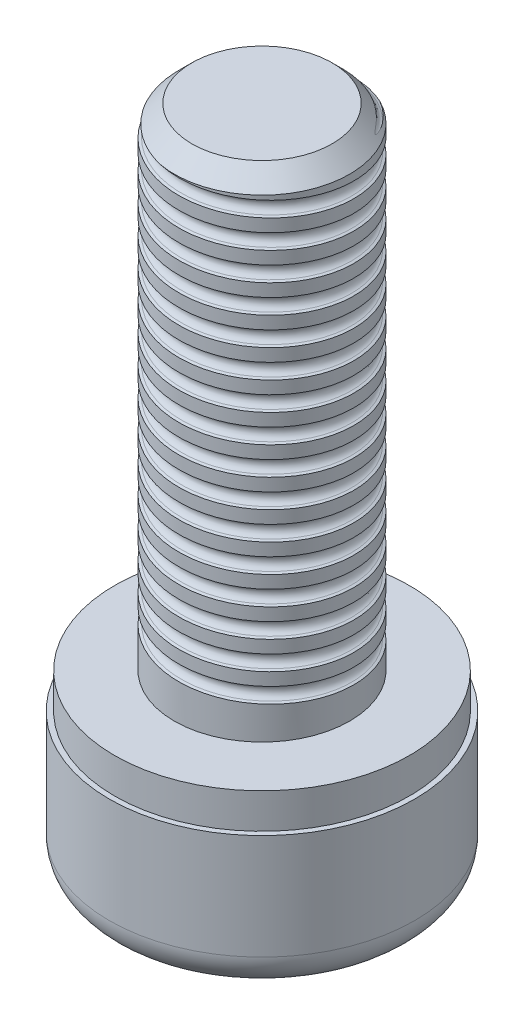
SolidWorks part; units mm, degrees
ref_plane "Спереди" through (0, 0, 0) normal (0, 0, 1) x (1, 0, 0)
ref_plane "Сверху" through (0, 0, 0) normal (0, 1, 0) x (1, 0, 0)
ref_plane "Справа" through (0, 0, 0) normal (1, 0, 0) x (0, 0, -1)
sketch "Эскиз1" plane through (0, 0, 0) normal (0, 1, 0) x (1, 0, 0)
  circle A0 centre (0, 0) radius 4.35
  dimension "D1" = 8.7
extrude "Бобышка-Вытянуть1" add sketch "Эскиз1" along normal blind 5
sketch "Эскиз2" plane through (0, 5, 0) normal (0, 1, 0) x (1, 0, 0)
  circle A0 centre (0, 0) radius 2.5
  dimension "D1" = 5
extrude "Бобышка-Вытянуть2" add sketch "Эскиз2" along normal blind 14
chamfer "Фаска1" distance 0.5 angle 45 1 edges at (0, 19, 2.5)
sketch "Эскиз3" plane through (0, 0, 0) normal (0, -1, 0) x (1, 0, 0)
  line L1 (1.9892, -1.1731) -> (2.0106, 1.1362)
  line L2 (2.0106, 1.1362) -> (0.0214, 2.3093)
  line L3 (0.0214, 2.3093) -> (-1.9892, 1.1731)
  line L4 (-1.9892, 1.1731) -> (-2.0106, -1.1362)
  line L5 (-2.0106, -1.1362) -> (-0.0214, -2.3093)
  line L6 (-0.0214, -2.3093) -> (1.9892, -1.1731)
  circle A0 centre (0, 0) radius 2 construction
  dimension "D1" = 4
extrude "Вырез-Вытянуть1" cut sketch "Эскиз3" against normal blind 2.5
fillet "Скругление1" radius 1 1 edges at (0, 0, 4.35)
sketch "Эскиз4" plane through (0, 5, 0) normal (0, 1, 0) x (1, 0, 0)
  circle A0 centre (0, 0) radius 4.2
  circle A1 centre (0, 0) radius 4.35
  dimension "D1" = 8.4
extrude "Вырез-Вытянуть3" cut sketch "Эскиз4" against normal blind 1
sketch "Эскиз7" plane through (0, 19, 0) normal (0, 1, 0) x (1, 0, 0)
  circle A0 centre (0, 0) radius 2.5
ref_plane "Плоскость2" through (0, 18.5, 0) normal (0, -1, 0) x (-1, 0, 0)
sketch "Эскиз8" plane through (0, 18.5, 0) normal (0, -1, 0) x (-1, 0, 0)
  circle A0 centre (0, 0) radius 2.5
curve "Спираль2" pitch 0.8 height 13.2 turns 16.5
sketch "Эскиз10" plane through (0, 0, 0) normal (0, 0, 1) x (1, 0, 0)
  line L0 (2.9, 16.8228) -> (2.9, 16.0949)
  line L1 (2.9, 16.0949) -> (2.4298, 16.266)
  line L2 (2.4298, 16.6517) -> (2.9, 16.8228)
  line L3 (2.9, 16.4589) -> (2.2948, 16.4589) construction
  arc A0 (2.4298, 16.6517) -> (2.4298, 16.266) centre (2.5, 16.4589) ccw
  dimension "D1" = 40
  dimension "D2" = 0.4702
  dimension "D3" = 0.4
  dimension "D4" = 2.9
sweep "Вырез-По траектории1" cut profiles "Эскиз10" path "Спираль2"
